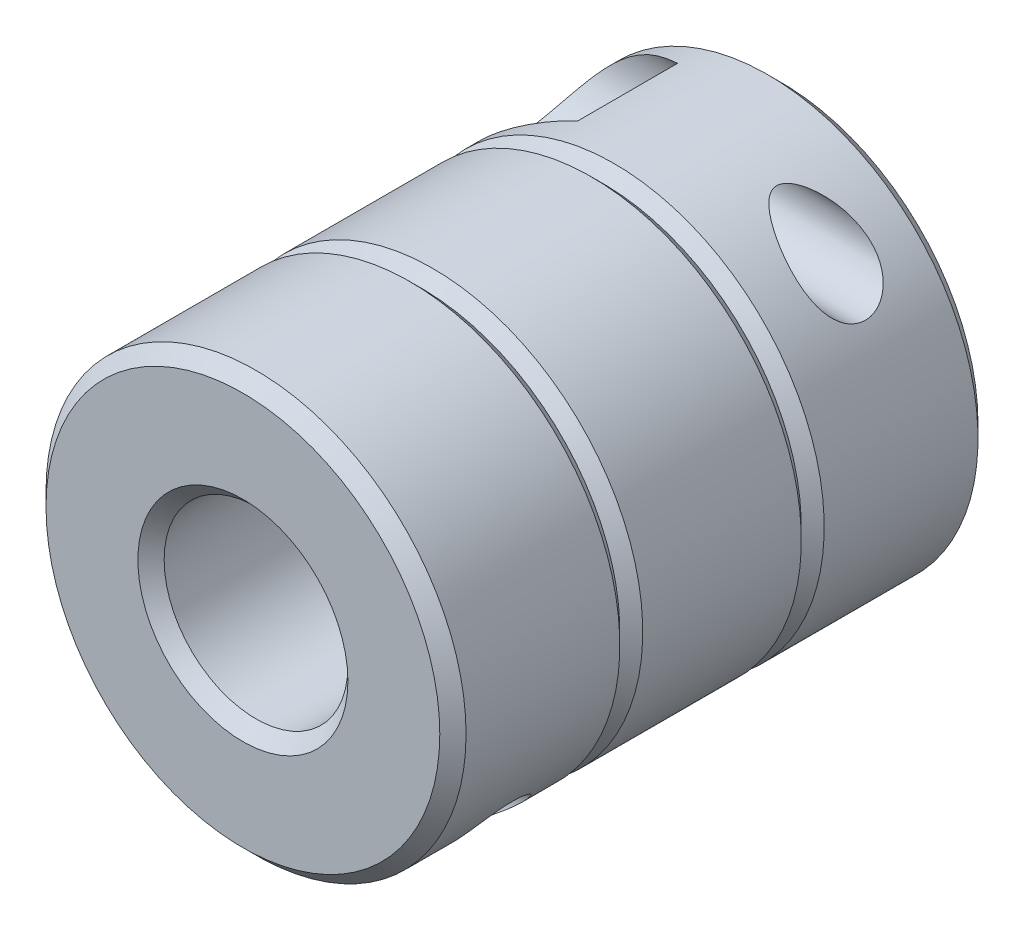
SolidWorks part; units mm, degrees
ref_plane "前视基准面" through (0, 0, 0) normal (0, 0, 1) x (1, 0, 0)
ref_plane "上视基准面" through (0, 0, 0) normal (0, 1, 0) x (1, 0, 0)
ref_plane "右视基准面" through (0, 0, 0) normal (1, 0, 0) x (0, 0, -1)
ref_plane "基准面4" through (0, 0, 0) normal (0, -1, 0) x (1, 0, 0)
sketch "草图1" plane through (0, 0, 0) normal (0, -1, 0) x (1, 0, 0)
  line L0 (16, 41) -> (0, 41)
  line L1 (0, 41) -> (0, 0)
  line L2 (0, 0) -> (16, 0)
  line L3 (16, 0) -> (16, 12.7161)
  line L4 (16, 12.7161) -> (15.1281, 13.588)
  line L5 (15.1281, 13.588) -> (16, 14.4598)
  line L6 (16, 14.4598) -> (16, 26.5402)
  line L7 (16, 26.5402) -> (15.1281, 27.412)
  line L8 (15.1281, 27.412) -> (16, 28.2839)
  line L9 (16, 28.2839) -> (16, 41)
  line L10 (0, 41) -> (0, 0) construction
revolve "旋转1" add sketch "草图1" angle 360 about L10
ref_plane "基准面5" through (-14.4168, 0, 0) normal (-1, 0, 0) x (0, 0, 1)
hole_wizard "M5 六角头螺栓的柱形沉头孔1" positions "草图3" profile "草图2" counterbore size "M5" standard "ANSI Metric"
sketch "草图3" plane through (-14.4168, 0, 0) normal (-1, 0, 0) x (0, 0, 1)
  point P0 (6.6804, 11.9395)
sketch "草图2" plane through (-14.4168, 11.9395, 6.6804) normal (0, 1, 0) x (0, 0, 1)
  line L0 (0, 0) -> (0, 30.4168)
  line L1 (0, 30.4168) -> (2.75, 30.4168)
  line L3 (2.75, 30.4168) -> (2.75, 9.4168)
  line L4 (2.75, 9.4168) -> (5, 9.4168)
  line L5 (5, 9.4168) -> (5, 0)
  line L7 (5, 0) -> (0, 0)
  line L11 (0, -6.35) -> (0, 107.95) construction
  dimension "通孔孔直径" = 5.5
  dimension "通孔孔深度" = 30.4168
  dimension "柱形沉头孔直径" = 10
  dimension "柱形沉头孔深度" = 9.4168
ref_plane "基准面6" through (-14.5375, 0, 0) normal (-1, 0, 0) x (0, 0, 1)
hole_wizard "M5 六角头螺栓的柱形沉头孔2" positions "草图5" profile "草图4" counterbore size "M5" standard "ANSI Metric"
sketch "草图5" plane through (-14.5375, 0, 0) normal (-1, 0, 0) x (0, 0, 1)
  point P0 (33.7201, -11.6828)
sketch "草图4" plane through (-14.5375, -11.6828, 33.7201) normal (0, 1, 0) x (0, 0, 1)
  line L0 (0, 0) -> (0, 30.5375)
  line L1 (0, 30.5375) -> (2.75, 30.5375)
  line L3 (2.75, 30.5375) -> (2.75, 9.5375)
  line L4 (2.75, 9.5375) -> (5, 9.5375)
  line L5 (5, 9.5375) -> (5, 0)
  line L7 (5, 0) -> (0, 0)
  line L11 (0, -6.35) -> (0, 107.95) construction
  dimension "通孔孔直径" = 5.5
  dimension "通孔孔深度" = 30.5375
  dimension "柱形沉头孔直径" = 10
  dimension "柱形沉头孔深度" = 9.5375
hole_wizard "Ø15.0 (15) 直径孔1" positions "草图7" profile "草图6" hole size "Ø15.0" standard "ANSI Metric"
sketch "草图7" plane through (0, 0, 0) normal (0, 0, -1) x (-1, 0, 0)
  point P0 (0, 0)
sketch "草图6" plane through (0, 0, 0) normal (1, 0, 0) x (0, 1, 0)
  line L0 (0, 0) -> (0, 20)
  line L1 (0, 20) -> (7.5, 20)
  line L2 (7.5, 20) -> (7.5, 0)
  line L5 (7.5, 0) -> (0, 0)
  line L10 (0, 20) -> (-7.5, 20) construction
  line L11 (0, -6.35) -> (0, 107.95) construction
  dimension "孔直径" = 15
  dimension "孔深度" = 20
  dimension "导头角度" = 180
hole_wizard "Ø14.0 (14) 直径孔1" positions "草图9" profile "草图8" hole size "Ø14.0" standard "ANSI Metric"
sketch "草图9" plane through (0, 0, 41) normal (0, 0, 1) x (1, 0, 0)
  point P0 (0, 0)
sketch "草图8" plane through (0, 0, 41) normal (1, 0, 0) x (0, -1, 0)
  line L0 (0, 0) -> (0, 20)
  line L1 (0, 20) -> (7, 20)
  line L2 (7, 20) -> (7, 0)
  line L5 (7, 0) -> (0, 0)
  line L10 (0, 20) -> (-7, 20) construction
  line L11 (0, -6.35) -> (0, 107.95) construction
  dimension "孔直径" = 14
  dimension "孔深度" = 20
  dimension "导头角度" = 180
chamfer "倒角1" distance 1 angle 45 4 edges at (-16, 0, 0) (-16, 0, 41) (7, 0, 41) (-7.5, 0, 0)
